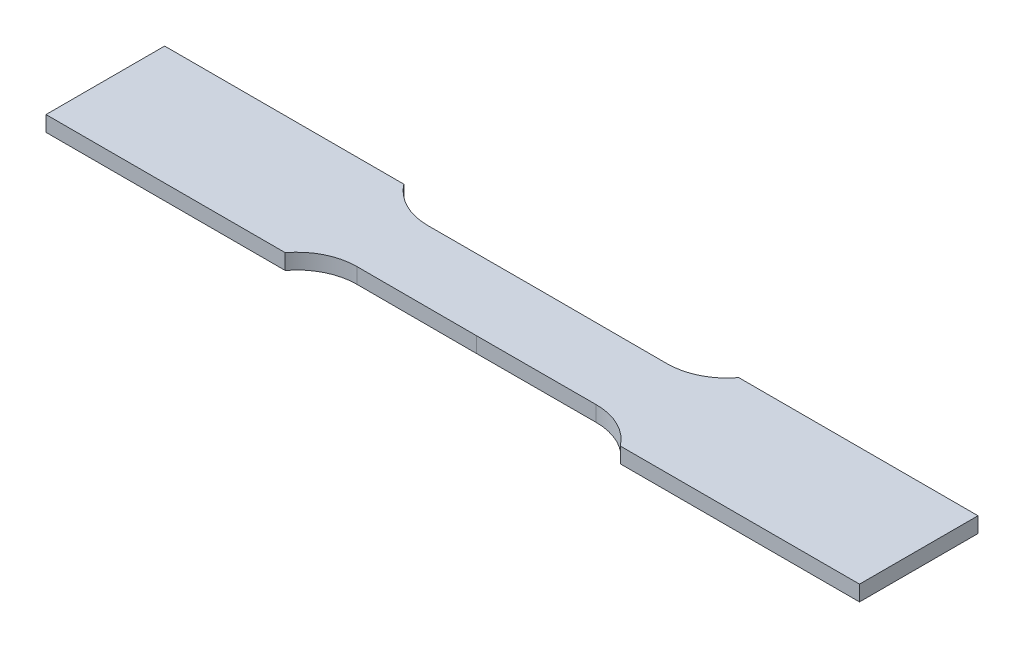
SolidWorks part; units mm, degrees
material "Copper"
ref_plane "Front Plane" through (0, 0, 0) normal (0, 0, 1) x (1, 0, 0)
ref_plane "Top Plane" through (0, 0, 0) normal (0, 1, 0) x (1, 0, 0)
ref_plane "Right Plane" through (0, 0, 0) normal (1, 0, 0) x (0, 0, -1)
sketch "Sketch1" plane through (0, 0, 0) normal (0, 1, 0) x (1, 0, 0)
  line L3 (25, 7.405) -> (0, 7.44)
  line L4 (0, 7.44) -> (-25, 7.415)
  line L5 (-25, -7.415) -> (0, -7.44)
  line L6 (0, -7.44) -> (25, -7.405)
  line L7 (0, 7.44) -> (0, -7.44) construction
  line L8 (-25, 0) -> (25, 0) construction
  line L9 (25, 7.405) -> (25, 12.3817) construction
  line L10 (-35, 12.3984) -> (-25, 12.3984) construction
  line L11 (-25, 12.3984) -> (-25, 7.415) construction
  line L12 (-25, -12.3984) -> (-25, -7.415) construction
  line L13 (-35, 12.3984) -> (-85, 12.3984)
  line L15 (-35, -12.3984) -> (-85, -12.3984)
  line L16 (-85, 12.3984) -> (-85, -12.3984)
  line L17 (25, 12.3817) -> (35, 12.3817) construction
  line L18 (-35, -12.3984) -> (-25, -12.3984) construction
  line L19 (-25, 7.415) -> (-25, -7.415) construction
  line L20 (25, -7.405) -> (25, 7.405) construction
  line L22 (25, -7.405) -> (25, -12.3817) construction
  line L23 (25, -12.3817) -> (35, -12.3817) construction
  line L24 (35, 12.3817) -> (85, 12.3817)
  line L26 (35, -12.3817) -> (85, -12.3817)
  line L27 (85, 12.3817) -> (85, -12.3817)
  arc A0 (-35, 12.3984) -> (-25, 7.415) centre (-25.0125, 19.915) ccw
  arc A1 (-35, -12.3984) -> (-25, -7.415) centre (-25.0125, -19.915) cw
  arc A2 (35, -12.3817) -> (25, -7.405) centre (25.0175, -19.905) ccw
  arc A3 (35, 12.3817) -> (25, 7.405) centre (25.0175, 19.905) cw
  point P2 (0, 0)
  point P11 (0, 0)
  point P12 (0, 0)
  point P14 (0, 0)
  point P18 (0, 0)
  dimension "D5" = 25
  dimension "D9" = 25
  dimension "D4" = 14.88
  dimension "D6" = 10
  dimension "D8" = 50
  dimension "D1" = 14.83
  dimension "D2" = 14.81
  dimension "D3" = 50
  dimension "D10" = 10
  dimension "D11" = 50
extrude "Boss-Extrude2" add sketch "Sketch1" along normal blind 3.227 contours L24 A3 L3 L4 A0 L13 L16 L15 A1 L5 L6 A2 L26 L27
equation "\"D5@Sketch1\"=12.5*2"
equation "\"D9@Sketch1\"=12.5*2"
